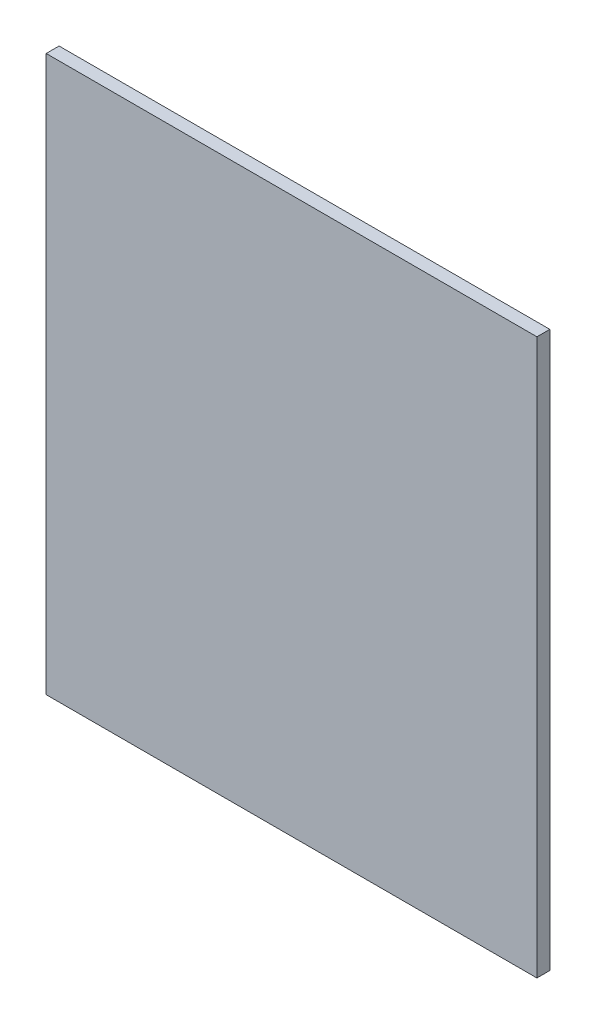
SolidWorks part; units mm, degrees
material "Balsa"
ref_plane "Front Plane" through (0, 0, 0) normal (0, 0, 1) x (1, 0, 0)
ref_plane "Top Plane" through (0, 0, 0) normal (0, 1, 0) x (1, 0, 0)
ref_plane "Right Plane" through (0, 0, 0) normal (1, 0, 0) x (0, 0, -1)
sketch "Sketch1" plane through (0, 0, 0) normal (0, 0, 1) x (1, 0, 0)
  line L1 (-241.3, -273.05) -> (241.3, -273.05)
  line L2 (-241.3, -273.05) -> (-241.3, 273.05)
  line L3 (-241.3, 273.05) -> (241.3, 273.05)
  line L4 (241.3, -273.05) -> (241.3, 273.05)
  line L5 (-241.3, -273.05) -> (241.3, 273.05) construction
  line L6 (-241.3, 273.05) -> (241.3, -273.05) construction
  point P0 (0, 0)
  dimension "D1" = 482.6
  dimension "D2" = 546.1
extrude "Boss-Extrude1" add sketch "Sketch1" along normal blind 12.7 contours L2 L1 L4 L3
